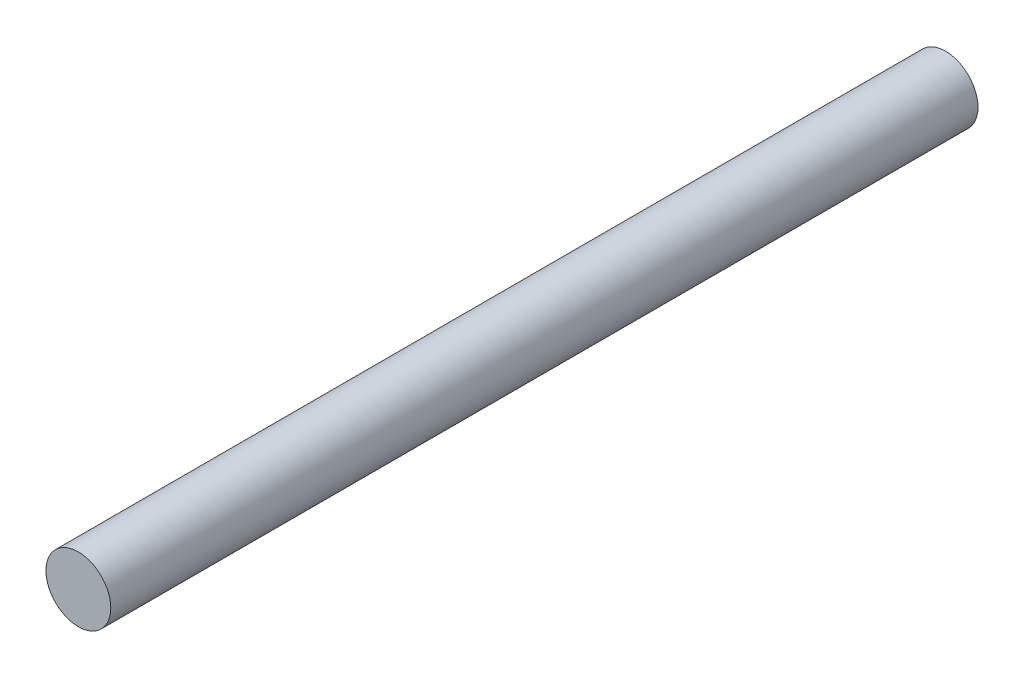
SolidWorks part; units mm, degrees
material "6063-T1"
ref_plane "Front Plane" through (0, 0, 0) normal (0, 0, 1) x (1, 0, 0)
ref_plane "Top Plane" through (0, 0, 0) normal (0, 1, 0) x (1, 0, 0)
ref_plane "Right Plane" through (0, 0, 0) normal (1, 0, 0) x (0, 0, -1)
sketch "Sketch1" plane through (0, 0, 0) normal (0, 0, 1) x (1, 0, 0)
  circle A0 centre (0, 0) radius 3
  dimension "D1" = 6
extrude "Boss-Extrude1" add sketch "Sketch1" along normal blind 80.26
